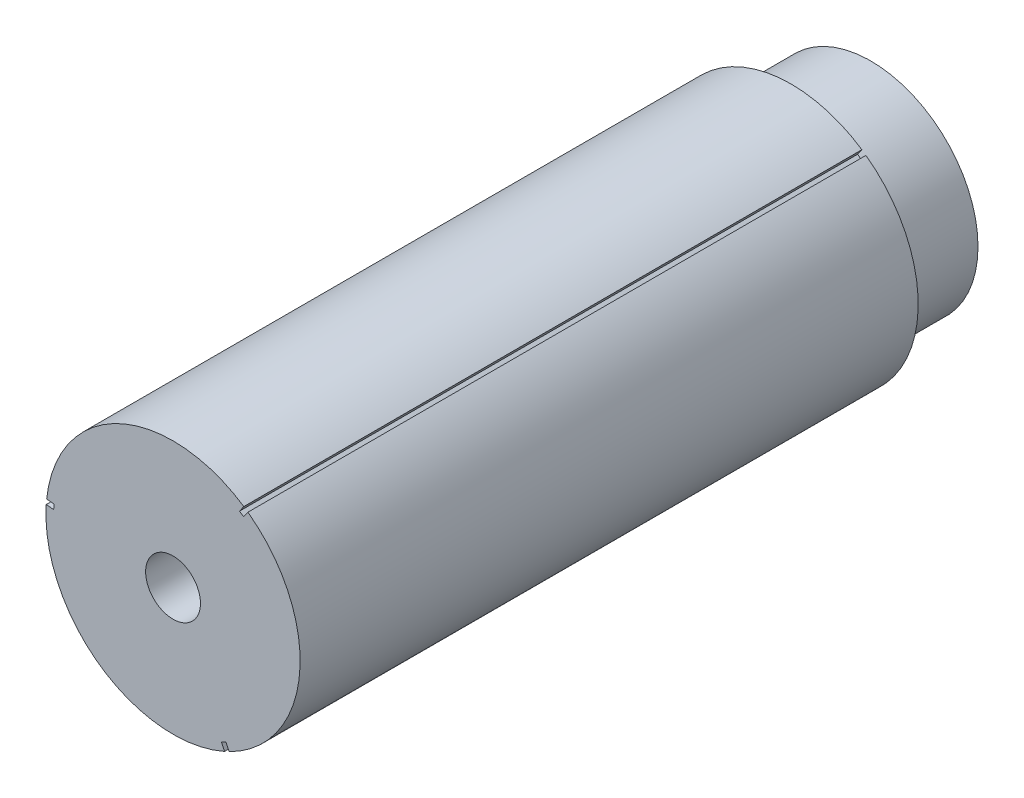
SolidWorks part; units mm, degrees
ref_plane "Face" through (0, 0, 0) normal (0, 0, 1) x (1, 0, 0)
ref_plane "Droite" through (0, 0, 0) normal (0, 1, 0) x (1, 0, 0)
ref_plane "Dessus" through (0, 0, 0) normal (1, 0, 0) x (0, 0, -1)
sketch "Esquisse1" plane through (0, 0, 0) normal (0, 0, 1) x (1, 0, 0)
  circle A0 centre (0, 0) radius 10.75
  circle A1 centre (0, 0) radius 2.75
  dimension "D1" = 21.5
  dimension "D2" = 5.5
extrude "Base-Extrusion" add sketch "Esquisse1" along normal blind 8
sketch "Esquisse2" plane through (0, 0, 8) normal (0, 0, 1) x (1, 0, 0)
  circle A0 centre (0, 0) radius 12.75
  circle A1 centre (0, 0) radius 2.75
  dimension "D1" = 25.5
  dimension "D2" = 5.5
extrude "Boss.-Extru.1" add sketch "Esquisse2" along normal blind 62
sketch "Esquisse4" plane through (0, 0, 70) normal (0, 0, 1) x (1, 0, 0)
  line L3 (7.1582, 10.6716) -> (6.6724, 9.977)
  line L4 (6.6724, 9.977) -> (7.0822, 9.6905)
  line L5 (7.0822, 9.6905) -> (7.5679, 10.3851)
  line L6 (7.1582, 10.6716) -> (6.6724, 9.977)
  line L7 (6.6724, 9.977) -> (7.0822, 9.6905)
  line L8 (7.0822, 9.6905) -> (7.5679, 10.3851)
  line L12 (5.6628, -11.535) -> (5.3042, -10.767)
  line L13 (5.3042, -10.767) -> (4.8511, -10.9786)
  line L14 (4.8511, -10.9786) -> (5.2098, -11.7465)
  line L15 (5.6628, -11.535) -> (5.3042, -10.767)
  line L16 (5.3042, -10.767) -> (4.8511, -10.9786)
  line L17 (4.8511, -10.9786) -> (5.2098, -11.7465)
  line L18 (-12.821, 0.8633) -> (-11.9766, 0.79)
  line L19 (-11.9766, 0.79) -> (-11.9333, 1.2881)
  line L20 (-11.9333, 1.2881) -> (-12.7777, 1.3615)
  line L21 (-12.821, 0.8633) -> (-11.9766, 0.79)
  line L22 (-11.9766, 0.79) -> (-11.9333, 1.2881)
  line L23 (-11.9333, 1.2881) -> (-12.7777, 1.3615)
  arc A1 (7.5679, 10.3851) -> (7.1582, 10.6716) centre (0, 0) ccw
  arc A2 (7.5679, 10.3851) -> (7.1582, 10.6716) centre (0, 0) ccw
  arc A4 (5.2098, -11.7465) -> (5.6628, -11.535) centre (0, 0) ccw
  arc A5 (5.2098, -11.7465) -> (5.6628, -11.535) centre (0, 0) ccw
  arc A6 (-12.7777, 1.3615) -> (-12.821, 0.8633) centre (0, 0) ccw
  arc A7 (-12.7777, 1.3615) -> (-12.821, 0.8633) centre (0, 0) ccw
  dimension "D1" = 0
  dimension "D2" = 0
  dimension "D3" = 0
extrude "Enlèv. mat.-Extru.1" cut sketch "Esquisse4" against normal up to next
